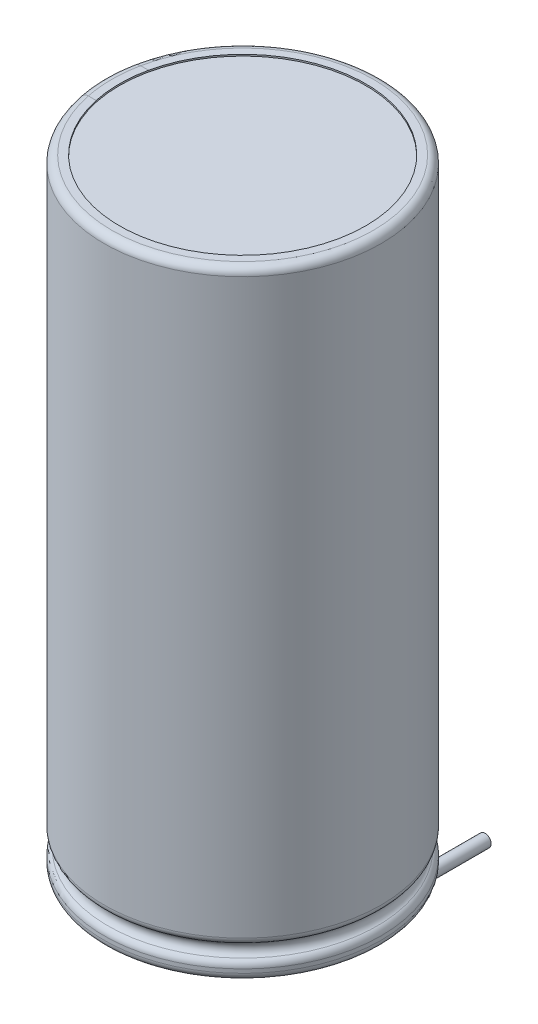
SolidWorks part; units mm, degrees
ref_plane "Front Plane" through (0, 0, 0) normal (0, 0, 1) x (1, 0, 0)
ref_plane "Top Plane" through (0, 0, 0) normal (0, 1, 0) x (1, 0, 0)
ref_plane "Right Plane" through (0, 0, 0) normal (1, 0, 0) x (0, 0, -1)
sketch "Sketch1" plane through (0, 0, 0) normal (0, 1, 0) x (1, 0, 0)
  line L0 (-3.75, -9) -> (3.75, -9) construction
  circle A0 centre (-3.75, -9) radius 0.4
  circle A1 centre (0, -9) radius 9 construction
  circle A2 centre (3.75, -9) radius 0.4
  point P2 (0, 0)
  dimension "D3" = 0.8
  dimension "D2" = 18
  dimension "D1" = 7.5
sketch "Эскиз1" plane through (0, 0, 0) normal (1, 0, 0) x (0, 0, -1)
  line L0 (-9, 0) -> (-9, -0.5)
  line L1 (-7, -2.5) -> (3, -2.5)
  line L2 (-9, 0) -> (-9, 1)
  arc A0 (-9, -0.5) -> (-7, -2.5) centre (-7, -0.5) ccw
  dimension "D3" = 2
  dimension "D1" = 3
  dimension "D2" = 2.5
  dimension "D4" = 1
sweep "По траектории1" add profiles "Sketch1" path "Эскиз1"
ref_plane "Плоскость1" through (0, 0, 9) normal (0, 0, 1) x (1, 0, 0)
sketch "Sketch3" plane through (0, 0, 9) normal (0, 0, 1) x (1, 0, 0)
  line L1 (0, 0.1) -> (0, 40.2) construction
  line L2 (9, 0.5) -> (9, 0.75)
  line L3 (0, 0.1) -> (8, 0.1)
  line L4 (8, 40.2) -> (8.5, 40.2)
  line L5 (8, 0) -> (8.5, 0)
  line L6 (0, 40.1) -> (8, 40.1)
  line L7 (9, 2.4821) -> (9, 39.7)
  line L8 (8, 40.1) -> (8, 40.2)
  line L9 (9, 2.4821) -> (9, 40.2) construction
  line L10 (8, 0) -> (8, 0.1)
  line L11 (0, 40.1) -> (9, 40.1) construction
  line L12 (0, 40.2) -> (9, 40.2) construction
  line L13 (8, 2.4821) -> (8, 40.2) construction
  line L14 (0, 0.1) -> (0, 40.1)
  line L17 (0, 0.1) -> (5, 0.1) construction
  line L18 (0, 0) -> (5, 0) construction
  arc A0 (8.75, 2.049) -> (8.75, 1.183) centre (9, 1.616) ccw
  arc A1 (9, 0.75) -> (8.75, 1.183) centre (8.5, 0.75) ccw
  arc A2 (9, 2.4821) -> (8.75, 2.049) centre (8.5, 2.4821) cw
  arc A3 (9, 39.7) -> (8.5, 40.2) centre (8.5, 39.7) ccw
  arc A4 (8.5, 0) -> (9, 0.5) centre (8.5, 0.5) ccw
  point P13 (9, 2.116)
  point P29 (0, 0)
  point P30 (9, 0)
  point P31 (0, 0)
  point P32 (8.5, 1.616)
  dimension "D2" = 0.5
  dimension "D1" = 0.5
  dimension "D3" = 40
  dimension "D6" = 1
  dimension "D7" = 0.1
  dimension "D10" = 0.25
  dimension "D11" = 16
  dimension "D12" = 17
  dimension "D5" = 1
revolve "Revolve1" add sketch "Sketch3" angle 360 about L14
sketch "Sketch4" plane through (0, 0, 0) normal (1, 0, 0) x (0, 0, -1)
  line L0 (-17.5, 0) -> (-0.5, 0) construction
  line L1 (-10.7, 0) -> (-7.3, 0)
  line L2 (-9, 0) -> (-9, 40.2) construction
  line L3 (-10.7, 40.2) -> (-7.3, 40.2)
  line L4 (-7.3, 0) -> (-7.3, 40.2)
  line L5 (-1, 40.2) -> (-17, 40.2) construction
  line L6 (-10.7, 0) -> (-10.7, 40.2)
  line L7 (-9.35, 13.3) -> (-9.35, 11.2)
  line L8 (-9.35, 13.3) -> (-8.65, 13.3)
  line L9 (-9, 13.3) -> (-9, 11.2) construction
  line L10 (-9.35, 11.2) -> (-8.65, 11.2)
  line L11 (-8.65, 13.3) -> (-8.65, 11.2)
  line L12 (-8.45, 13.5) -> (-8.45, 11)
  line L13 (-9.55, 11) -> (-8.45, 11)
  line L14 (-9.55, 13.5) -> (-9.55, 11)
  line L15 (-9.55, 13.5) -> (-8.45, 13.5)
  line L17 (-9.35, 8.3) -> (-9.35, 6.2)
  line L18 (-9.35, 8.3) -> (-8.65, 8.3)
  line L19 (-9.35, 6.2) -> (-8.65, 6.2)
  line L20 (-8.65, 8.3) -> (-8.65, 6.2)
  line L21 (-8.45, 8.5) -> (-8.45, 6)
  line L22 (-9.55, 6) -> (-8.45, 6)
  line L23 (-9.55, 8.5) -> (-9.55, 6)
  line L24 (-9.55, 8.5) -> (-8.45, 8.5)
  line L25 (-9, 8.3) -> (-9, 6.2) construction
  line L26 (-9.35, 3.3) -> (-9.35, 1.2)
  line L27 (-9.35, 3.3) -> (-8.65, 3.3)
  line L28 (-9.35, 1.2) -> (-8.65, 1.2)
  line L29 (-8.65, 3.3) -> (-8.65, 1.2)
  line L30 (-8.45, 3.5) -> (-8.45, 1)
  line L31 (-9.55, 1) -> (-8.45, 1)
  line L32 (-9.55, 3.5) -> (-9.55, 1)
  line L33 (-9.55, 3.5) -> (-8.45, 3.5)
  line L34 (-9, 3.3) -> (-9, 1.2) construction
  line L35 (-9.55, 18.5) -> (-8.45, 18.5)
  line L36 (-9.55, 18.5) -> (-9.55, 16)
  line L37 (-9.35, 18.3) -> (-8.65, 18.3)
  line L38 (-8.65, 18.3) -> (-8.65, 16.2)
  line L39 (-8.45, 18.5) -> (-8.45, 16)
  line L40 (-9.35, 18.3) -> (-9.35, 16.2)
  line L41 (-9.35, 16.2) -> (-8.65, 16.2)
  line L42 (-9.55, 16) -> (-8.45, 16)
  line L43 (-9.55, 23.5) -> (-8.45, 23.5)
  line L44 (-9.55, 23.5) -> (-9.55, 21)
  line L45 (-9.35, 23.3) -> (-8.65, 23.3)
  line L46 (-8.65, 23.3) -> (-8.65, 21.2)
  line L47 (-8.45, 23.5) -> (-8.45, 21)
  line L48 (-9.35, 23.3) -> (-9.35, 21.2)
  line L49 (-9.35, 21.2) -> (-8.65, 21.2)
  line L50 (-9.55, 21) -> (-8.45, 21)
  line L51 (-9.55, 11) -> (-9.55, 8.5) construction
  line L52 (-9.55, 13.5) -> (-9.55, 16) construction
  line L53 (-9.55, 28.5) -> (-8.45, 28.5)
  line L54 (-9.55, 28.5) -> (-9.55, 26)
  line L55 (-9.35, 28.3) -> (-8.65, 28.3)
  line L56 (-8.65, 28.3) -> (-8.65, 26.2)
  line L57 (-8.45, 28.5) -> (-8.45, 26)
  line L58 (-9.35, 28.3) -> (-9.35, 26.2)
  line L59 (-9.35, 26.2) -> (-8.65, 26.2)
  line L60 (-9.55, 26) -> (-8.45, 26)
  line L61 (-9.55, 33.5) -> (-8.45, 33.5)
  line L62 (-9.55, 33.5) -> (-9.55, 31)
  line L63 (-9.35, 33.3) -> (-8.65, 33.3)
  line L64 (-8.65, 33.3) -> (-8.65, 31.2)
  line L65 (-8.45, 33.5) -> (-8.45, 31)
  line L66 (-9.35, 33.3) -> (-9.35, 31.2)
  line L67 (-9.35, 31.2) -> (-8.65, 31.2)
  line L68 (-9.55, 31) -> (-8.45, 31)
  line L69 (-9.55, 38.5) -> (-8.45, 38.5)
  line L70 (-9.55, 38.5) -> (-9.55, 36)
  line L71 (-9.35, 38.3) -> (-8.65, 38.3)
  line L72 (-8.65, 38.3) -> (-8.65, 36.2)
  line L73 (-8.45, 38.5) -> (-8.45, 36)
  line L74 (-9.35, 38.3) -> (-9.35, 36.2)
  line L75 (-9.35, 36.2) -> (-8.65, 36.2)
  line L76 (-9.55, 36) -> (-8.45, 36)
  point P64 (-9, 18.3)
  dimension "D5" = 3.4
  dimension "D6" = 0.2
  dimension "D7" = 1.1
  dimension "D8" = 2.1
  dimension "D1" = 0.7
  dimension "D9" = 1
  dimension "D10" = 2.5
  dimension "D2" = 3
  dimension "D3" = 6
split line "Split Line1"
